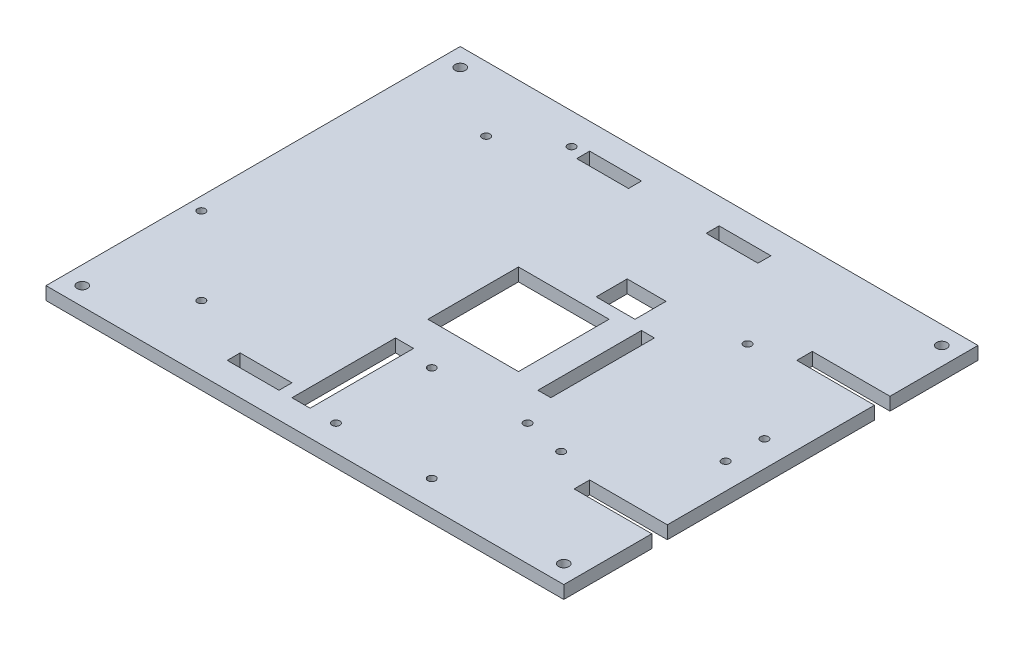
SolidWorks part; units mm, degrees
ref_plane "Front Plane" through (0, 0, 0) normal (0, 0, 1) x (1, 0, 0)
ref_plane "Top Plane" through (0, 0, 0) normal (0, 1, 0) x (1, 0, 0)
ref_plane "Right Plane" through (0, 0, 0) normal (1, 0, 0) x (0, 0, -1)
sketch "Sketch1" plane through (0, 0, 0) normal (0, 1, 0) x (1, 0, 0)
  line L1 (-100, 80) -> (100, 80)
  line L2 (-100, 80) -> (-100, -80)
  line L3 (-100, -80) -> (100, -80)
  line L4 (100, 80) -> (100, -80)
  line L5 (-100, 80) -> (100, -80) construction
  line L6 (-100, -80) -> (100, 80) construction
  point P0 (0, 0)
  dimension "D1" = 200
  dimension "D2" = 160
extrude "Boss-Extrude1" add sketch "Sketch1" along normal blind 5
sketch "Sketch2" plane through (0, 5, 0) normal (0, 1, 0) x (1, 0, 0)
  line L0 (-100, 0) -> (100, 0) construction
  line L1 (-100, 80) -> (-100, -80) construction
  line L2 (100, -80) -> (100, 80) construction
  line L4 (100, 80) -> (-100, 80) construction
  line L5 (0, 80) -> (0, -76.5866) construction
  circle A0 centre (-93, 73) radius 2
  circle A1 centre (93, 73) radius 2
  circle A2 centre (93, -73) radius 2
  circle A3 centre (-93, -73) radius 2
  dimension "D1" = 4
  dimension "D2" = 7
  dimension "D3" = 7
extrude "Cut-Extrude1" cut sketch "Sketch2" against normal blind 5
sketch "Sketch3" plane through (0, 5, 0) normal (0, 1, 0) x (1, 0, 0)
  line L0 (-100, 0) -> (110.5314, 0) construction
  line L1 (-100, 80) -> (-100, -80) construction
  line L2 (100, -80) -> (100, 80) construction
  line L3 (100, 80) -> (-100, 80) construction
  line L4 (0, 80) -> (0, -80) construction
  line L5 (-100, -80) -> (100, -80) construction
  circle A0 centre (90, 7.5) radius 1.5
  circle A1 centre (90, -7.5) radius 1.5
  dimension "D1" = 15
  dimension "D2" = 10
  dimension "D3" = 3
extrude "Cut-Extrude4" cut sketch "Sketch3" against normal blind 5
sketch "Sketch4" plane through (0, 5, 0) normal (0, 1, 0) x (1, 0, 0)
  line L0 (-100, 0) -> (119.321, 0) construction
  line L1 (-100, 80) -> (-100, -80) construction
  line L2 (100, -80) -> (100, 80) construction
  line L3 (100, 80) -> (-100, 80) construction
  line L4 (0, 80) -> (0, -80) construction
  line L5 (-100, -80) -> (100, -80) construction
  circle A0 centre (55, 36) radius 1.5
  circle A1 centre (55, -36) radius 1.5
  dimension "D1" = 45
  dimension "D2" = 3
  dimension "D3" = 72
extrude "Cut-Extrude5" cut sketch "Sketch4" against normal blind 5
sketch "Sketch5" plane through (0, 5, 0) normal (0, 1, 0) x (1, 0, 0)
  line L0 (-100, 0) -> (100, 0) construction
  line L1 (-100, 80) -> (-100, -80) construction
  line L2 (100, -80) -> (100, 80) construction
  line L4 (100, 80) -> (-100, 80) construction
  line L5 (0, 80) -> (0, -80) construction
  line L6 (-100, -80) -> (100, -80) construction
  line L7 (20, 17.5) -> (-15, 17.5)
  line L8 (20, 17.5) -> (20, -17.5)
  line L9 (20, -17.5) -> (-15, -17.5)
  line L10 (-15, 17.5) -> (-15, -17.5)
  line L11 (20, 17.5) -> (-15, -17.5) construction
  line L12 (20, -17.5) -> (-15, 17.5) construction
  point P6 (2.5, 0)
  dimension "D1" = 80
  dimension "D2" = 35
  dimension "D3" = 35
  dimension "D4" = 0
extrude "Cut-Extrude6" cut sketch "Sketch5" against normal blind 5
sketch "Sketch6" plane through (0, 5, 0) normal (0, 1, 0) x (1, 0, 0)
  line L0 (-98.249, 0) -> (100, 0) construction
  line L1 (100, -80) -> (100, 80) construction
  line L3 (-100, -80) -> (100, -80) construction
  line L4 (0, -80) -> (0, 80) construction
  line L5 (100, 80) -> (-100, 80) construction
sketch "Sketch7" plane through (0, 5, 0) normal (0, 1, 0) x (1, 0, 0)
  line L0 (-100, -80) -> (100, -80) construction
  line L1 (-15, -30) -> (-8, -30)
  line L2 (-15, -30) -> (-15, -70)
  line L3 (-15, -70) -> (-8, -70)
  line L4 (-8, -30) -> (-8, -70)
  line L5 (100, -80) -> (100, 80) construction
  line L6 (-98.249, 0) -> (100, 0) construction
  line L7 (30, 20) -> (35, 20)
  line L8 (30, 20) -> (30, -20)
  line L9 (30, -20) -> (35, -20)
  line L10 (35, 20) -> (35, -20)
  line L11 (30, 20) -> (35, -20) construction
  line L12 (30, -20) -> (35, 20) construction
  line L13 (-98.249, 0) -> (100, 0) construction
  line L14 (-100, 80) -> (-100, -80) construction
  line L15 (-40, 70) -> (-20, 70)
  line L16 (-40, 70) -> (-40, 65)
  line L17 (-40, 65) -> (-20, 65)
  line L18 (-20, 70) -> (-20, 65)
  line L19 (-40, 70) -> (-20, 65) construction
  line L20 (-40, 65) -> (-20, 70) construction
  line L21 (100, 80) -> (-100, 80) construction
  line L22 (-40, -65) -> (-20, -65)
  line L23 (-20, -70) -> (-20, -65)
  line L24 (-40, -70) -> (-40, -65)
  line L25 (-40, -70) -> (-20, -70)
  point P8 (32.5, 0)
  point P25 (-30, 67.5)
  dimension "D1" = 7
  dimension "D2" = 40
  dimension "D3" = 10
  dimension "D4" = 108
  dimension "D5" = 5
  dimension "D6" = 70
  dimension "D7" = 40
  dimension "D10" = 60
  dimension "D11" = 20
  dimension "D12" = 12.5
  dimension "D13" = 5
extrude "Cut-Extrude7" cut sketch "Sketch7" against normal blind 5
sketch "Sketch8" plane through (0, 5, 0) normal (0, 1, 0) x (1, 0, 0)
  line L0 (20, 17.5) -> (-15, 17.5) construction
  line L1 (10, 34.5) -> (25, 34.5)
  line L2 (10, 34.5) -> (10, 22.5)
  line L3 (10, 22.5) -> (25, 22.5)
  line L4 (25, 34.5) -> (25, 22.5)
  line L5 (10, 34.5) -> (25, 22.5) construction
  line L6 (10, 22.5) -> (25, 34.5) construction
  line L7 (100, -80) -> (100, 80) construction
  line L8 (-98.249, 0) -> (100, 0) construction
  line L9 (100, 46) -> (70, 46)
  line L10 (100, 46) -> (100, 40)
  line L11 (100, 40) -> (70, 40)
  line L12 (70, 46) -> (70, 40)
  line L13 (100, -46) -> (100, -40)
  line L14 (70, -46) -> (70, -40)
  line L15 (100, -40) -> (70, -40)
  line L16 (100, -46) -> (70, -46)
  point P0 (17.5, 28.5)
  dimension "D1" = 12
  dimension "D2" = 15
  dimension "D3" = 5
  dimension "D4" = 75
  dimension "D5" = 6
  dimension "D6" = 40
  dimension "D7" = 30
extrude "Cut-Extrude8" cut sketch "Sketch8" against normal blind 5
sketch "Sketch9" plane through (0, 5, 0) normal (0, 1, 0) x (1, 0, 0)
  line L0 (100, 46) -> (100, 80) construction
  line L1 (10, 70) -> (30, 70)
  line L2 (10, 70) -> (10, 65)
  line L3 (10, 65) -> (30, 65)
  line L4 (30, 70) -> (30, 65)
  line L5 (100, 80) -> (-100, 80) construction
  point P4 (100, 63)
  dimension "D1" = 20
  dimension "D2" = 5
  dimension "D3" = 70
  dimension "D4" = 10
extrude "Cut-Extrude9" cut sketch "Sketch9" against normal blind 5
sketch "Sketch10" plane through (0, 5, 0) normal (0, 1, 0) x (1, 0, 0)
  line L0 (-100, -80) -> (100, -80) construction
  line L1 (-100, 80) -> (-100, -80) construction
  line L2 (100, 80) -> (-100, 80) construction
  circle A0 centre (-95, -25) radius 1.5
  circle A1 centre (-45, 68) radius 1.5
  dimension "D1" = 55
  dimension "D2" = 3
  dimension "D3" = 5
  dimension "D4" = 3
  dimension "D5" = 12
  dimension "D6" = 55
extrude "Cut-Extrude10" cut sketch "Sketch10" against normal blind 5
sketch "Sketch11" plane through (0, 5, 0) normal (0, 1, 0) x (1, 0, 0)
  line L0 (-8, -70) -> (-8, -30) construction
  line L1 (-100, -80) -> (100, -80) construction
  line L2 (2, -51.5) -> (59.0967, -51.5) construction
  line L3 (20.5, -24.2001) -> (20.5, -71.6632) construction
  circle A0 centre (2, -33) radius 1.5
  circle A1 centre (2, -70) radius 1.5
  circle A2 centre (39, -70) radius 1.5
  circle A3 centre (39, -33) radius 1.5
  dimension "D1" = 10
  dimension "D2" = 47
  dimension "D3" = 3
  dimension "D4" = 18.5
  dimension "D5" = 18.5
extrude "Cut-Extrude11" cut sketch "Sketch11" against normal blind 5
sketch "Sketch12" plane through (0, 5, 0) normal (0, 1, 0) x (1, 0, 0)
  line L0 (-65, 80) -> (-65, -83.2106) construction
  line L1 (100, 80) -> (-100, 80) construction
  line L2 (-100, 80) -> (-100, -80) construction
  line L3 (-98.249, 0) -> (104.7756, 0) construction
  circle A0 centre (-65, 55) radius 1.5
  circle A1 centre (-65, -55) radius 1.5
  dimension "D3" = 3
  dimension "D1" = 35
  dimension "D2" = 25
extrude "Cut-Extrude12" cut sketch "Sketch12" against normal blind 5
